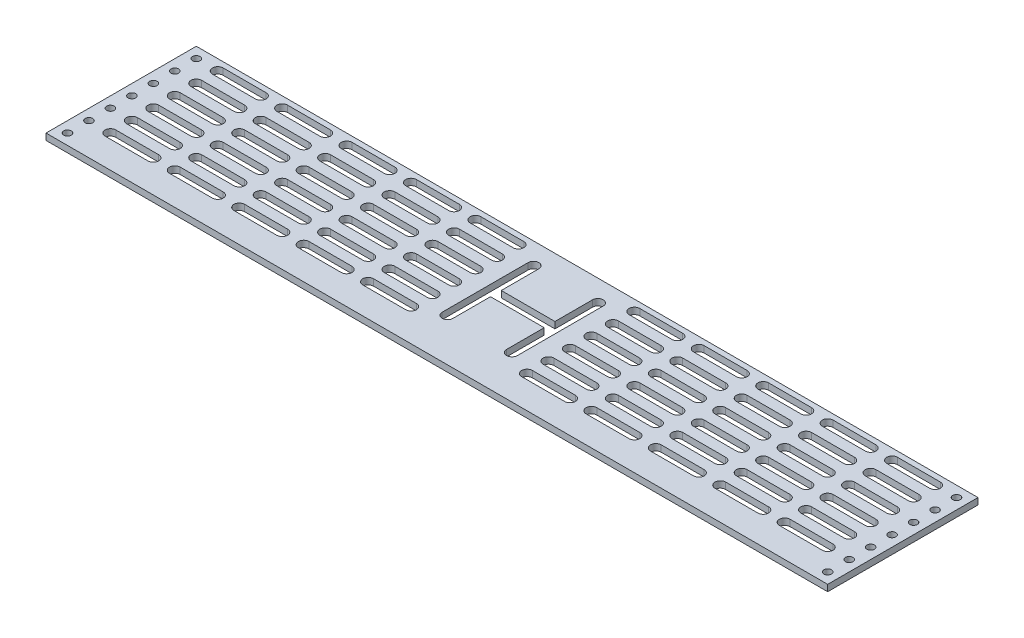
SolidWorks part; units mm, degrees
material "A-玻璃纤维"
ref_plane "前视基准面" through (0, 0, 0) normal (0, 0, 1) x (1, 0, 0)
ref_plane "上视基准面" through (0, 0, 0) normal (0, 1, 0) x (1, 0, 0)
ref_plane "右视基准面" through (0, 0, 0) normal (1, 0, 0) x (0, 0, -1)
other "Configuration Table"
sketch "草图1" plane through (0, 0, 0) normal (0, 1, 0) x (1, 0, 0)
  line L0 (0, 0) -> (-182, 0)
  line L1 (0, 0) -> (182, 0)
  line L2 (182, 0) -> (182, -80)
  line L3 (182, -80) -> (-182, -80)
  line L4 (-182, -80) -> (-182, 0)
extrude "凸台-拉伸1" add sketch "草图1" along normal blind 3
sketch "草图2" plane through (0, 3, 0) normal (0, 1, 0) x (1, 0, 0)
  line L0 (-182, -80) -> (-177, -80)
  line L1 (-182, -80) -> (182, -80) construction
  line L2 (-177, -80) -> (-177, 0)
  line L3 (182, 0) -> (-182, 0) construction
  line L4 (-177, -80) -> (-177, -75)
  line L5 (0, 0) -> (0, -80)
  circle A0 centre (-177, -75) radius 1.75
  circle A1 centre (-177, -65) radius 1.75
  circle A2 centre (-177, -55) radius 1.75
  circle A3 centre (-177, -45) radius 1.75
  circle A4 centre (-177, -35) radius 1.75
  circle A5 centre (-177, -25) radius 1.75
  circle A6 centre (-177, -15) radius 1.75
  circle A7 centre (-177, -5) radius 1.75
  circle A8 centre (177, -5) radius 1.75
  circle A9 centre (177, -15) radius 1.75
  circle A10 centre (177, -25) radius 1.75
  circle A11 centre (177, -35) radius 1.75
  circle A12 centre (177, -45) radius 1.75
  circle A13 centre (177, -55) radius 1.75
  circle A14 centre (177, -65) radius 1.75
  circle A15 centre (177, -75) radius 1.75
  dimension "D1" = 8
  dimension "D2" = 3.5
  dimension "D3" = 5
extrude "切除-拉伸1" cut sketch "草图2" against normal through all contours L4 A0 L2 | L2 A0 L4 | L2 A1 | L2 A1 | L2 A2 | L2 A2 | L2 A3 | L2 A3 | L2 A4 | L2 A4 | L2 A5 | L2 A5 | L2 A6 | L2 A6 | L2 A7 | L2 A7 | A8 | A9 | A10 | A11 | A12 | A13 | A14 | A15
sketch "草图3" plane through (0, 3, 0) normal (0, 1, 0) x (1, 0, 0)
  line L0 (0, 0) -> (0, -80)
  line L1 (182, 0) -> (-182, 0) construction
  line L2 (-182, -80) -> (182, -80) construction
  line L3 (0, -40) -> (-15, -40)
  line L4 (0, -40) -> (15, -40)
  line L5 (15, -40) -> (15, -20)
  line L6 (15, -40) -> (15, -60)
  line L7 (-15, -40) -> (-15, -20)
  line L8 (-15, -40) -> (-15, -60)
  line L9 (-15, -40) -> (15, -40) construction
  line L10 (-12.5, -37.5) -> (12.5, -37.5)
  line L11 (-12.5, -42.5) -> (12.5, -42.5)
  line L12 (-15, -20) -> (-15, -60) construction
  line L13 (-12.5, -20) -> (-12.5, -37.5)
  line L14 (-17.5, -20) -> (-17.5, -60)
  line L15 (15, -20) -> (15, -60) construction
  line L16 (17.5, -20) -> (17.5, -60)
  line L17 (12.5, -20) -> (12.5, -37.5)
  line L18 (12.5, -42.5) -> (12.5, -60)
  line L19 (-12.5, -42.5) -> (-12.5, -60)
  line L20 (-182, -80) -> (0, -80)
  line L21 (-91, -80) -> (-91, 0)
  line L22 (-177, -65) -> (-91, -65)
  line L23 (-177, -65) -> (-167, -65)
  line L24 (-167, -65) -> (-147, -65)
  line L25 (-147, -65) -> (-137, -65)
  line L26 (-137, -65) -> (-117, -65)
  line L27 (-117, -65) -> (-107, -65)
  line L28 (-107, -65) -> (-87, -65)
  line L29 (-87, -65) -> (-77, -65)
  line L30 (-77, -65) -> (-57, -65)
  line L31 (-167, -65) -> (-147, -65) construction
  line L32 (-167, -62.5) -> (-147, -62.5)
  line L33 (-167, -67.5) -> (-147, -67.5)
  line L34 (-137, -65) -> (-117, -65) construction
  line L35 (-137, -62.5) -> (-117, -62.5)
  line L36 (-137, -67.5) -> (-117, -67.5)
  line L37 (-107, -65) -> (-87, -65) construction
  line L38 (-107, -62.5) -> (-87, -62.5)
  line L39 (-107, -67.5) -> (-87, -67.5)
  line L40 (-77, -65) -> (-57, -65) construction
  line L41 (-77, -62.5) -> (-57, -62.5)
  line L42 (-77, -67.5) -> (-57, -67.5)
  line L43 (-167, -57.5) -> (-147, -57.5)
  line L44 (-167, -52.5) -> (-147, -52.5)
  line L45 (-137, -57.5) -> (-117, -57.5)
  line L46 (-137, -52.5) -> (-117, -52.5)
  line L47 (-107, -57.5) -> (-87, -57.5)
  line L48 (-107, -52.5) -> (-87, -52.5)
  line L49 (-77, -57.5) -> (-57, -57.5)
  line L50 (-77, -52.5) -> (-57, -52.5)
  line L51 (-167, -55) -> (-147, -55) construction
  line L52 (-137, -55) -> (-117, -55) construction
  line L53 (-107, -55) -> (-87, -55) construction
  line L54 (-77, -55) -> (-57, -55) construction
  line L55 (-167, -47.5) -> (-147, -47.5)
  line L56 (-167, -42.5) -> (-147, -42.5)
  line L57 (-137, -47.5) -> (-117, -47.5)
  line L58 (-137, -42.5) -> (-117, -42.5)
  line L59 (-107, -47.5) -> (-87, -47.5)
  line L60 (-107, -42.5) -> (-87, -42.5)
  line L61 (-77, -47.5) -> (-57, -47.5)
  line L62 (-77, -42.5) -> (-57, -42.5)
  line L63 (-167, -45) -> (-147, -45) construction
  line L64 (-137, -45) -> (-117, -45) construction
  line L65 (-107, -45) -> (-87, -45) construction
  line L66 (-77, -45) -> (-57, -45) construction
  line L67 (-167, -37.5) -> (-147, -37.5)
  line L68 (-167, -32.5) -> (-147, -32.5)
  line L69 (-137, -37.5) -> (-117, -37.5)
  line L70 (-137, -32.5) -> (-117, -32.5)
  line L71 (-107, -37.5) -> (-87, -37.5)
  line L72 (-107, -32.5) -> (-87, -32.5)
  line L73 (-77, -37.5) -> (-57, -37.5)
  line L74 (-77, -32.5) -> (-57, -32.5)
  line L75 (-167, -35) -> (-147, -35) construction
  line L76 (-137, -35) -> (-117, -35) construction
  line L77 (-107, -35) -> (-87, -35) construction
  line L78 (-77, -35) -> (-57, -35) construction
  line L79 (-167, -27.5) -> (-147, -27.5)
  line L80 (-167, -22.5) -> (-147, -22.5)
  line L81 (-137, -27.5) -> (-117, -27.5)
  line L82 (-137, -22.5) -> (-117, -22.5)
  line L83 (-107, -27.5) -> (-87, -27.5)
  line L84 (-107, -22.5) -> (-87, -22.5)
  line L85 (-77, -27.5) -> (-57, -27.5)
  line L86 (-77, -22.5) -> (-57, -22.5)
  line L87 (-167, -25) -> (-147, -25) construction
  line L88 (-137, -25) -> (-117, -25) construction
  line L89 (-107, -25) -> (-87, -25) construction
  line L90 (-77, -25) -> (-57, -25) construction
  line L91 (-167, -17.5) -> (-147, -17.5)
  line L92 (-167, -12.5) -> (-147, -12.5)
  line L93 (-137, -17.5) -> (-117, -17.5)
  line L94 (-137, -12.5) -> (-117, -12.5)
  line L95 (-107, -17.5) -> (-87, -17.5)
  line L96 (-107, -12.5) -> (-87, -12.5)
  line L97 (-77, -17.5) -> (-57, -17.5)
  line L98 (-77, -12.5) -> (-57, -12.5)
  line L99 (-167, -15) -> (-147, -15) construction
  line L100 (-137, -15) -> (-117, -15) construction
  line L101 (-107, -15) -> (-87, -15) construction
  line L102 (-77, -15) -> (-57, -15) construction
  line L103 (87, -65) -> (77, -65)
  line L104 (107, -65) -> (87, -65)
  line L105 (117, -65) -> (107, -65)
  line L106 (137, -65) -> (117, -65)
  line L107 (147, -65) -> (137, -65)
  line L108 (167, -65) -> (147, -65)
  line L109 (77, -15) -> (57, -15) construction
  line L110 (77, -12.5) -> (57, -12.5)
  line L111 (77, -17.5) -> (57, -17.5)
  line L112 (107, -15) -> (87, -15) construction
  line L113 (107, -12.5) -> (87, -12.5)
  line L114 (107, -17.5) -> (87, -17.5)
  line L115 (137, -15) -> (117, -15) construction
  line L116 (137, -12.5) -> (117, -12.5)
  line L117 (137, -17.5) -> (117, -17.5)
  line L118 (77, -25) -> (57, -25) construction
  line L119 (77, -22.5) -> (57, -22.5)
  line L120 (77, -27.5) -> (57, -27.5)
  line L121 (107, -25) -> (87, -25) construction
  line L122 (107, -22.5) -> (87, -22.5)
  line L123 (107, -27.5) -> (87, -27.5)
  line L124 (137, -25) -> (117, -25) construction
  line L125 (137, -22.5) -> (117, -22.5)
  line L126 (137, -27.5) -> (117, -27.5)
  line L127 (77, -35) -> (57, -35) construction
  line L128 (77, -32.5) -> (57, -32.5)
  line L129 (77, -37.5) -> (57, -37.5)
  line L130 (107, -35) -> (87, -35) construction
  line L131 (107, -32.5) -> (87, -32.5)
  line L132 (107, -37.5) -> (87, -37.5)
  line L133 (137, -35) -> (117, -35) construction
  line L134 (137, -32.5) -> (117, -32.5)
  line L135 (137, -37.5) -> (117, -37.5)
  line L136 (167, -35) -> (147, -35) construction
  line L137 (167, -32.5) -> (147, -32.5)
  line L138 (167, -37.5) -> (147, -37.5)
  line L139 (77, -45) -> (57, -45) construction
  line L140 (77, -42.5) -> (57, -42.5)
  line L141 (77, -47.5) -> (57, -47.5)
  line L142 (107, -45) -> (87, -45) construction
  line L143 (107, -42.5) -> (87, -42.5)
  line L144 (107, -47.5) -> (87, -47.5)
  line L145 (137, -45) -> (117, -45) construction
  line L146 (137, -42.5) -> (117, -42.5)
  line L147 (137, -47.5) -> (117, -47.5)
  line L148 (167, -45) -> (147, -45) construction
  line L149 (167, -42.5) -> (147, -42.5)
  line L150 (167, -47.5) -> (147, -47.5)
  line L151 (77, -55) -> (57, -55) construction
  line L152 (77, -52.5) -> (57, -52.5)
  line L153 (77, -57.5) -> (57, -57.5)
  line L154 (107, -55) -> (87, -55) construction
  line L155 (107, -52.5) -> (87, -52.5)
  line L156 (107, -57.5) -> (87, -57.5)
  line L157 (137, -55) -> (117, -55) construction
  line L158 (137, -52.5) -> (117, -52.5)
  line L159 (137, -57.5) -> (117, -57.5)
  line L160 (167, -55) -> (147, -55) construction
  line L161 (167, -52.5) -> (147, -52.5)
  line L162 (167, -57.5) -> (147, -57.5)
  line L163 (77, -65) -> (57, -65) construction
  line L164 (77, -62.5) -> (57, -62.5)
  line L165 (77, -67.5) -> (57, -67.5)
  line L166 (107, -65) -> (87, -65) construction
  line L167 (107, -62.5) -> (87, -62.5)
  line L168 (107, -67.5) -> (87, -67.5)
  line L169 (137, -65) -> (117, -65) construction
  line L170 (137, -62.5) -> (117, -62.5)
  line L171 (137, -67.5) -> (117, -67.5)
  line L172 (167, -65) -> (147, -65) construction
  line L173 (167, -62.5) -> (147, -62.5)
  line L174 (167, -67.5) -> (147, -67.5)
  line L175 (167, -25) -> (147, -25) construction
  line L176 (167, -22.5) -> (147, -22.5)
  line L177 (167, -27.5) -> (147, -27.5)
  line L178 (167, -15) -> (147, -15) construction
  line L179 (167, -12.5) -> (147, -12.5)
  line L180 (167, -17.5) -> (147, -17.5)
  line L181 (-57, -65) -> (-47, -65)
  line L182 (-47, -65) -> (-27, -65)
  line L183 (-47, -65) -> (-27, -65) construction
  line L184 (-47, -62.5) -> (-27, -62.5)
  line L185 (-47, -67.5) -> (-27, -67.5)
  line L186 (-47, -57.5) -> (-27, -57.5)
  line L187 (-47, -52.5) -> (-27, -52.5)
  line L188 (-47, -55) -> (-27, -55) construction
  line L189 (-47, -47.5) -> (-27, -47.5)
  line L190 (-47, -42.5) -> (-27, -42.5)
  line L191 (-47, -45) -> (-27, -45) construction
  line L192 (-47, -37.5) -> (-27, -37.5)
  line L193 (-47, -32.5) -> (-27, -32.5)
  line L194 (-47, -35) -> (-27, -35) construction
  line L195 (-47, -27.5) -> (-27, -27.5)
  line L196 (-47, -22.5) -> (-27, -22.5)
  line L197 (-47, -25) -> (-27, -25) construction
  line L198 (-47, -17.5) -> (-27, -17.5)
  line L199 (-47, -12.5) -> (-27, -12.5)
  line L200 (-47, -15) -> (-27, -15) construction
  line L201 (47, -65) -> (27, -65)
  line L202 (47, -15) -> (27, -15) construction
  line L203 (47, -12.5) -> (27, -12.5)
  line L204 (47, -17.5) -> (27, -17.5)
  line L205 (47, -25) -> (27, -25) construction
  line L206 (47, -22.5) -> (27, -22.5)
  line L207 (47, -27.5) -> (27, -27.5)
  line L208 (47, -35) -> (27, -35) construction
  line L209 (47, -32.5) -> (27, -32.5)
  line L210 (47, -37.5) -> (27, -37.5)
  line L211 (47, -45) -> (27, -45) construction
  line L212 (47, -42.5) -> (27, -42.5)
  line L213 (47, -47.5) -> (27, -47.5)
  line L214 (47, -55) -> (27, -55) construction
  line L215 (47, -52.5) -> (27, -52.5)
  line L216 (47, -57.5) -> (27, -57.5)
  line L217 (47, -65) -> (27, -65) construction
  line L218 (47, -62.5) -> (27, -62.5)
  line L219 (47, -67.5) -> (27, -67.5)
  arc A2 (-12.5, -20) -> (-17.5, -20) centre (-15, -20) ccw
  arc A3 (-17.5, -60) -> (-12.5, -60) centre (-15, -60) ccw
  arc A4 (17.5, -20) -> (12.5, -20) centre (15, -20) ccw
  arc A5 (12.5, -60) -> (17.5, -60) centre (15, -60) ccw
  arc A6 (-167, -62.5) -> (-167, -67.5) centre (-167, -65) ccw
  arc A7 (-147, -67.5) -> (-147, -62.5) centre (-147, -65) ccw
  arc A8 (-137, -62.5) -> (-137, -67.5) centre (-137, -65) ccw
  arc A9 (-117, -67.5) -> (-117, -62.5) centre (-117, -65) ccw
  arc A10 (-107, -62.5) -> (-107, -67.5) centre (-107, -65) ccw
  arc A11 (-87, -67.5) -> (-87, -62.5) centre (-87, -65) ccw
  arc A12 (-77, -62.5) -> (-77, -67.5) centre (-77, -65) ccw
  arc A13 (-57, -67.5) -> (-57, -62.5) centre (-57, -65) ccw
  arc A14 (-167, -52.5) -> (-167, -57.5) centre (-167, -55) ccw
  arc A15 (-147, -57.5) -> (-147, -52.5) centre (-147, -55) ccw
  arc A16 (-137, -52.5) -> (-137, -57.5) centre (-137, -55) ccw
  arc A17 (-117, -57.5) -> (-117, -52.5) centre (-117, -55) ccw
  arc A18 (-107, -52.5) -> (-107, -57.5) centre (-107, -55) ccw
  arc A19 (-87, -57.5) -> (-87, -52.5) centre (-87, -55) ccw
  arc A20 (-77, -52.5) -> (-77, -57.5) centre (-77, -55) ccw
  arc A21 (-57, -57.5) -> (-57, -52.5) centre (-57, -55) ccw
  arc A22 (-167, -42.5) -> (-167, -47.5) centre (-167, -45) ccw
  arc A23 (-147, -47.5) -> (-147, -42.5) centre (-147, -45) ccw
  arc A24 (-137, -42.5) -> (-137, -47.5) centre (-137, -45) ccw
  arc A25 (-117, -47.5) -> (-117, -42.5) centre (-117, -45) ccw
  arc A26 (-107, -42.5) -> (-107, -47.5) centre (-107, -45) ccw
  arc A27 (-87, -47.5) -> (-87, -42.5) centre (-87, -45) ccw
  arc A28 (-77, -42.5) -> (-77, -47.5) centre (-77, -45) ccw
  arc A29 (-57, -47.5) -> (-57, -42.5) centre (-57, -45) ccw
  arc A30 (-167, -32.5) -> (-167, -37.5) centre (-167, -35) ccw
  arc A31 (-147, -37.5) -> (-147, -32.5) centre (-147, -35) ccw
  arc A32 (-137, -32.5) -> (-137, -37.5) centre (-137, -35) ccw
  arc A33 (-117, -37.5) -> (-117, -32.5) centre (-117, -35) ccw
  arc A34 (-107, -32.5) -> (-107, -37.5) centre (-107, -35) ccw
  arc A35 (-87, -37.5) -> (-87, -32.5) centre (-87, -35) ccw
  arc A36 (-77, -32.5) -> (-77, -37.5) centre (-77, -35) ccw
  arc A37 (-57, -37.5) -> (-57, -32.5) centre (-57, -35) ccw
  arc A38 (-167, -22.5) -> (-167, -27.5) centre (-167, -25) ccw
  arc A39 (-147, -27.5) -> (-147, -22.5) centre (-147, -25) ccw
  arc A40 (-137, -22.5) -> (-137, -27.5) centre (-137, -25) ccw
  arc A41 (-117, -27.5) -> (-117, -22.5) centre (-117, -25) ccw
  arc A42 (-107, -22.5) -> (-107, -27.5) centre (-107, -25) ccw
  arc A43 (-87, -27.5) -> (-87, -22.5) centre (-87, -25) ccw
  arc A44 (-77, -22.5) -> (-77, -27.5) centre (-77, -25) ccw
  arc A45 (-57, -27.5) -> (-57, -22.5) centre (-57, -25) ccw
  arc A46 (-167, -12.5) -> (-167, -17.5) centre (-167, -15) ccw
  arc A47 (-147, -17.5) -> (-147, -12.5) centre (-147, -15) ccw
  arc A48 (-137, -12.5) -> (-137, -17.5) centre (-137, -15) ccw
  arc A49 (-117, -17.5) -> (-117, -12.5) centre (-117, -15) ccw
  arc A50 (-107, -12.5) -> (-107, -17.5) centre (-107, -15) ccw
  arc A51 (-87, -17.5) -> (-87, -12.5) centre (-87, -15) ccw
  arc A52 (-77, -12.5) -> (-77, -17.5) centre (-77, -15) ccw
  arc A53 (-57, -17.5) -> (-57, -12.5) centre (-57, -15) ccw
  arc A54 (77, -12.5) -> (77, -17.5) centre (77, -15) cw
  arc A55 (57, -17.5) -> (57, -12.5) centre (57, -15) cw
  arc A56 (107, -12.5) -> (107, -17.5) centre (107, -15) cw
  arc A57 (87, -17.5) -> (87, -12.5) centre (87, -15) cw
  arc A58 (137, -12.5) -> (137, -17.5) centre (137, -15) cw
  arc A59 (117, -17.5) -> (117, -12.5) centre (117, -15) cw
  arc A60 (77, -22.5) -> (77, -27.5) centre (77, -25) cw
  arc A61 (57, -27.5) -> (57, -22.5) centre (57, -25) cw
  arc A62 (107, -22.5) -> (107, -27.5) centre (107, -25) cw
  arc A63 (87, -27.5) -> (87, -22.5) centre (87, -25) cw
  arc A64 (137, -22.5) -> (137, -27.5) centre (137, -25) cw
  arc A65 (117, -27.5) -> (117, -22.5) centre (117, -25) cw
  arc A66 (77, -32.5) -> (77, -37.5) centre (77, -35) cw
  arc A67 (57, -37.5) -> (57, -32.5) centre (57, -35) cw
  arc A68 (107, -32.5) -> (107, -37.5) centre (107, -35) cw
  arc A69 (87, -37.5) -> (87, -32.5) centre (87, -35) cw
  arc A70 (137, -32.5) -> (137, -37.5) centre (137, -35) cw
  arc A71 (117, -37.5) -> (117, -32.5) centre (117, -35) cw
  arc A72 (167, -32.5) -> (167, -37.5) centre (167, -35) cw
  arc A73 (147, -37.5) -> (147, -32.5) centre (147, -35) cw
  arc A74 (77, -42.5) -> (77, -47.5) centre (77, -45) cw
  arc A75 (57, -47.5) -> (57, -42.5) centre (57, -45) cw
  arc A76 (107, -42.5) -> (107, -47.5) centre (107, -45) cw
  arc A77 (87, -47.5) -> (87, -42.5) centre (87, -45) cw
  arc A78 (137, -42.5) -> (137, -47.5) centre (137, -45) cw
  arc A79 (117, -47.5) -> (117, -42.5) centre (117, -45) cw
  arc A80 (167, -42.5) -> (167, -47.5) centre (167, -45) cw
  arc A81 (147, -47.5) -> (147, -42.5) centre (147, -45) cw
  arc A82 (77, -52.5) -> (77, -57.5) centre (77, -55) cw
  arc A83 (57, -57.5) -> (57, -52.5) centre (57, -55) cw
  arc A84 (107, -52.5) -> (107, -57.5) centre (107, -55) cw
  arc A85 (87, -57.5) -> (87, -52.5) centre (87, -55) cw
  arc A86 (137, -52.5) -> (137, -57.5) centre (137, -55) cw
  arc A87 (117, -57.5) -> (117, -52.5) centre (117, -55) cw
  arc A88 (167, -52.5) -> (167, -57.5) centre (167, -55) cw
  arc A89 (147, -57.5) -> (147, -52.5) centre (147, -55) cw
  arc A90 (77, -62.5) -> (77, -67.5) centre (77, -65) cw
  arc A91 (57, -67.5) -> (57, -62.5) centre (57, -65) cw
  arc A92 (107, -62.5) -> (107, -67.5) centre (107, -65) cw
  arc A93 (87, -67.5) -> (87, -62.5) centre (87, -65) cw
  arc A94 (137, -62.5) -> (137, -67.5) centre (137, -65) cw
  arc A95 (117, -67.5) -> (117, -62.5) centre (117, -65) cw
  arc A96 (167, -62.5) -> (167, -67.5) centre (167, -65) cw
  arc A97 (147, -67.5) -> (147, -62.5) centre (147, -65) cw
  arc A98 (167, -22.5) -> (167, -27.5) centre (167, -25) cw
  arc A99 (147, -27.5) -> (147, -22.5) centre (147, -25) cw
  arc A100 (167, -12.5) -> (167, -17.5) centre (167, -15) cw
  arc A101 (147, -17.5) -> (147, -12.5) centre (147, -15) cw
  arc A102 (-47, -62.5) -> (-47, -67.5) centre (-47, -65) ccw
  arc A103 (-27, -67.5) -> (-27, -62.5) centre (-27, -65) ccw
  arc A104 (-47, -52.5) -> (-47, -57.5) centre (-47, -55) ccw
  arc A105 (-27, -57.5) -> (-27, -52.5) centre (-27, -55) ccw
  arc A106 (-47, -42.5) -> (-47, -47.5) centre (-47, -45) ccw
  arc A107 (-27, -47.5) -> (-27, -42.5) centre (-27, -45) ccw
  arc A108 (-47, -32.5) -> (-47, -37.5) centre (-47, -35) ccw
  arc A109 (-27, -37.5) -> (-27, -32.5) centre (-27, -35) ccw
  arc A110 (-47, -22.5) -> (-47, -27.5) centre (-47, -25) ccw
  arc A111 (-27, -27.5) -> (-27, -22.5) centre (-27, -25) ccw
  arc A112 (-47, -12.5) -> (-47, -17.5) centre (-47, -15) ccw
  arc A113 (-27, -17.5) -> (-27, -12.5) centre (-27, -15) ccw
  arc A114 (47, -12.5) -> (47, -17.5) centre (47, -15) cw
  arc A115 (27, -17.5) -> (27, -12.5) centre (27, -15) cw
  arc A116 (47, -22.5) -> (47, -27.5) centre (47, -25) cw
  arc A117 (27, -27.5) -> (27, -22.5) centre (27, -25) cw
  arc A118 (47, -32.5) -> (47, -37.5) centre (47, -35) cw
  arc A119 (27, -37.5) -> (27, -32.5) centre (27, -35) cw
  arc A120 (47, -42.5) -> (47, -47.5) centre (47, -45) cw
  arc A121 (27, -47.5) -> (27, -42.5) centre (27, -45) cw
  arc A122 (47, -52.5) -> (47, -57.5) centre (47, -55) cw
  arc A123 (27, -57.5) -> (27, -52.5) centre (27, -55) cw
  arc A124 (47, -62.5) -> (47, -67.5) centre (47, -65) cw
  arc A125 (27, -67.5) -> (27, -62.5) centre (27, -65) cw
  point P8 (0, -40)
  point P18 (-15, -40)
  point P23 (15, -40)
  point P43 (-157, -65)
  point P48 (-127, -65)
  point P53 (-97, -65)
  point P58 (-67, -65)
  point P73 (-157, -55)
  point P78 (-127, -55)
  point P83 (-97, -55)
  point P88 (-67, -55)
  point P101 (-157, -45)
  point P106 (-127, -45)
  point P111 (-97, -45)
  point P116 (-67, -45)
  point P129 (-157, -35)
  point P134 (-127, -35)
  point P139 (-97, -35)
  point P144 (-67, -35)
  point P157 (-157, -25)
  point P162 (-127, -25)
  point P167 (-97, -25)
  point P172 (-67, -25)
  point P185 (-157, -15)
  point P190 (-127, -15)
  point P195 (-97, -15)
  point P200 (-67, -15)
  point P212 (67, -15)
  point P219 (97, -15)
  point P226 (127, -15)
  point P233 (67, -25)
  point P240 (97, -25)
  point P247 (127, -25)
  point P254 (67, -35)
  point P261 (97, -35)
  point P268 (127, -35)
  point P275 (157, -35)
  point P282 (67, -45)
  point P289 (97, -45)
  point P296 (127, -45)
  point P303 (157, -45)
  point P310 (67, -55)
  point P317 (97, -55)
  point P324 (127, -55)
  point P331 (157, -55)
  point P337 (67, -65)
  point P342 (97, -65)
  point P347 (127, -65)
  point P352 (157, -65)
  point P359 (157, -25)
  point P366 (157, -15)
  point P374 (-37, -65)
  point P383 (-37, -55)
  point P390 (-37, -45)
  point P397 (-37, -35)
  point P404 (-37, -25)
  point P411 (-37, -15)
  point P418 (37, -15)
  point P425 (37, -25)
  point P432 (37, -35)
  point P439 (37, -45)
  point P446 (37, -55)
  point P451 (37, -65)
  dimension "D3" = 6
  dimension "D4" = 6
  dimension "D1" = 15
  dimension "D2" = 15
extrude "切除-拉伸2" cut sketch "草图3" against normal through all
sketch "草图4" plane through (0, 0, 0) normal (0, -1, 0) x (1, 0, 0)
  line L0 (177, 15) -> (177, 10)
  line L1 (177, 10) -> (187.2333, 10)
  line L2 (182, 0) -> (182.1166, 10)
  line L3 (182.1166, 10) -> (-182, 10)
  line L4 (-182, 0) -> (-182, 80) construction
  line L5 (-182, 10) -> (-182, 0)
  line L6 (-182, 0) -> (182, 0)
extrude "切除-拉伸3" cut sketch "草图4" against normal blind 10 contours L5 L6 L2 L1 L3
